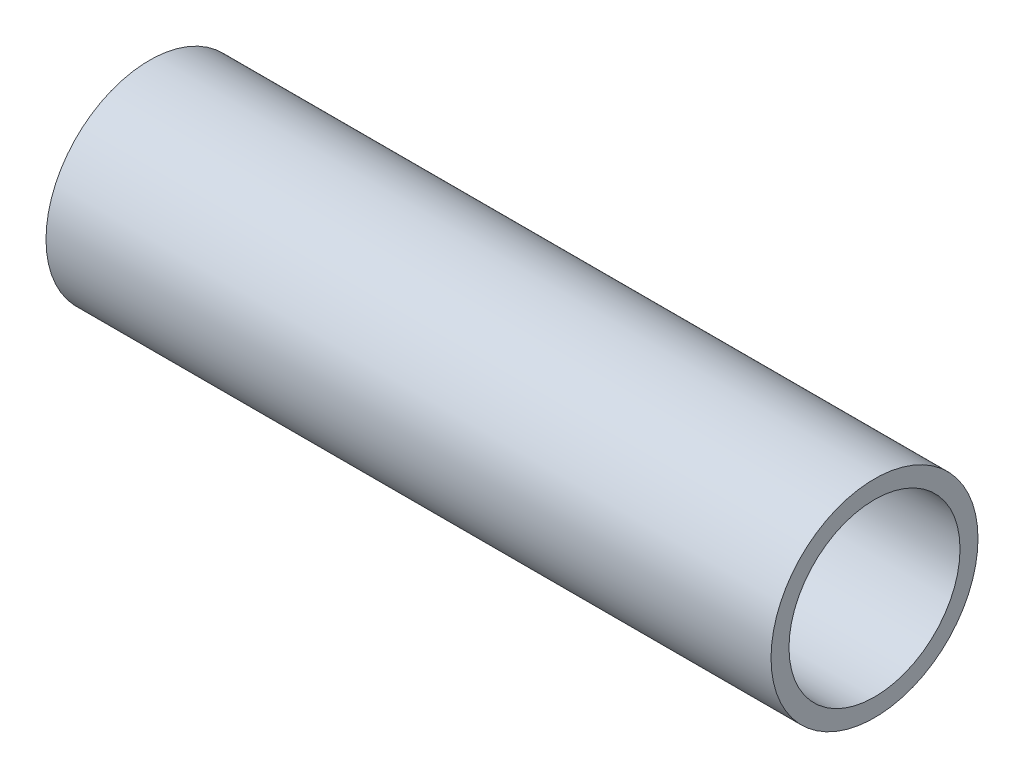
SolidWorks part; units mm, degrees
material "ASTM A106"
ref_plane "Front Plane" through (0, 0, 0) normal (0, 0, 1) x (1, 0, 0)
ref_plane "Top Plane" through (0, 0, 0) normal (0, 1, 0) x (1, 0, 0)
ref_plane "Right Plane" through (0, 0, 0) normal (1, 0, 0) x (0, 0, -1)
sketch "Sketch1" plane through (0, 0, 0) normal (1, 0, 0) x (0, 0, -1)
  circle A0 centre (0, 0) radius 16.7
  circle A1 centre (0, 0) radius 13.8
  dimension "D1" = 33.4
  dimension "D2" = 27.6
extrude "Boss-Extrude1" add sketch "Sketch1" along normal blind 117
